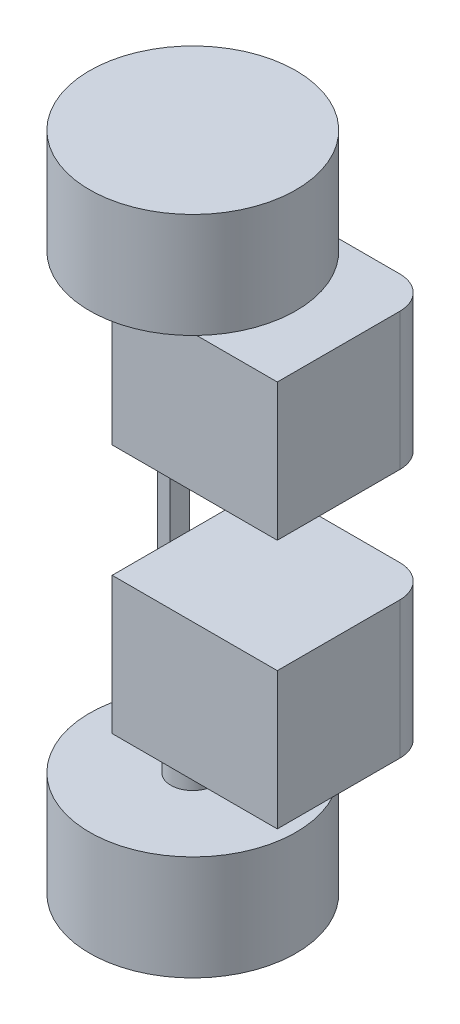
SolidWorks part; units mm, degrees
ref_plane "前视基准面" through (0, 0, 0) normal (0, 0, 1) x (1, 0, 0)
ref_plane "上视基准面" through (0, 0, 0) normal (0, 1, 0) x (1, 0, 0)
ref_plane "右视基准面" through (0, 0, 0) normal (1, 0, 0) x (0, 0, -1)
sketch "草图1" plane through (0, 0, 0) normal (0, 1, 0) x (1, 0, 0)
  line L1 (0, 0) -> (51.2, 0)
  line L2 (0, 0) -> (0, 48)
  line L3 (0, 48) -> (51.2, 48)
  line L4 (51.2, 0) -> (51.2, 48)
  dimension "D1" = 51.2
  dimension "D2" = 48
extrude "凸台-拉伸1" add sketch "草图1" along normal blind 120
fillet "圆角1" radius 10 1 edges at (51.2, 60, -48)
sketch "草图3" plane through (0, 0, 0) normal (0, -1, 0) x (1, 0, 0)
  line L0 (0, 0) -> (51.2, 0) construction
  line L1 (0, -48) -> (0, 0) construction
  circle A0 centre (13, -12) radius 6.8039
  dimension "D1" = 12
  dimension "D2" = 13
extrude "凸台-拉伸2" add sketch "草图3" along normal blind 10
sketch "草图4" plane through (0, -10, 0) normal (0, -1, 0) x (1, 0, 0)
  circle A0 centre (13, -12) radius 32
  dimension "D1" = 64
extrude "凸台-拉伸3" add sketch "草图4" along normal blind 32.5
ref_plane "基准面1" through (0, 60, 0) normal (0, -1, 0) x (-1, 0, 0)
mirror "镜向1" about plane through (0, 60, 0) normal (0, -1, 0) of "凸台-拉伸3", "凸台-拉伸2"
sketch "草图5" plane through (0, 0, 0) normal (-1, 0, 0) x (0, 0, 1)
  line L0 (-48, 60) -> (0, 60) construction
  line L1 (-48, 120) -> (-48, 0) construction
  line L2 (0, 120) -> (0, 0) construction
  line L4 (-48, 42.5) -> (0, 42.5)
  line L5 (-48, 42.5) -> (-48, 77.5)
  line L6 (-48, 77.5) -> (0, 77.5)
  line L7 (0, 42.5) -> (0, 77.5)
  line L8 (-48, 42.5) -> (0, 77.5) construction
  line L9 (-48, 77.5) -> (0, 42.5) construction
  point P4 (-24, 60)
  dimension "D1" = 35
extrude "切除-拉伸1" cut sketch "草图5" against normal through all
sketch "草图6" plane through (0, 0, 0) normal (-1, 0, 0) x (0, 0, 1)
  line L1 (-24, 0) -> (-18, 0)
  line L2 (-24, 0) -> (-24, 120)
  line L3 (-24, 120) -> (-18, 120)
  line L4 (-18, 0) -> (-18, 120)
  line L5 (-24, 0) -> (-18, 120) construction
  line L6 (-24, 120) -> (-18, 0) construction
  line L7 (0, 42.5) -> (0, 0) construction
  line L8 (-48, 0) -> (0, 0) construction
  point P0 (-21, 60)
  dimension "D1" = 6
  dimension "D2" = 120
  dimension "D4" = 18
extrude "凸台-拉伸6" add sketch "草图6" along normal blind 4
